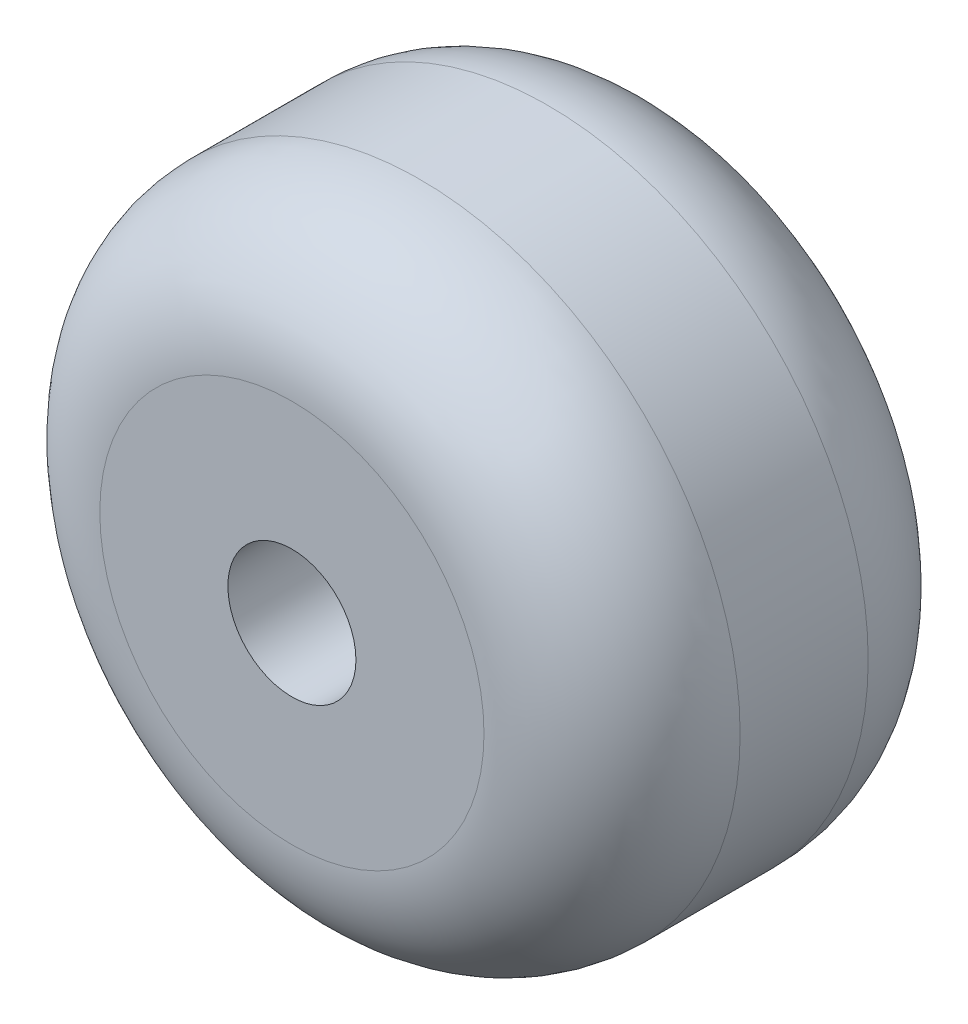
SolidWorks part; units mm, degrees
ref_plane "Front Plane" through (0, 0, 0) normal (0, 0, 1) x (1, 0, 0)
ref_plane "Top Plane" through (0, 0, 0) normal (0, 1, 0) x (1, 0, 0)
ref_plane "Right Plane" through (0, 0, 0) normal (1, 0, 0) x (0, 0, -1)
sketch "Sketch1" plane through (0, 0, 0) normal (0, 0, 1) x (1, 0, 0)
  circle A0 centre (0, 0) radius 25
  circle A1 centre (0, 0) radius 5
  dimension "D1" = 50
  dimension "D2" = 10
extrude "Boss-Extrude1" add sketch "Sketch1" along normal blind 30
fillet "Fillet1" radius 10 2 edges at (25, 0, 0) (25, 0, 30)
